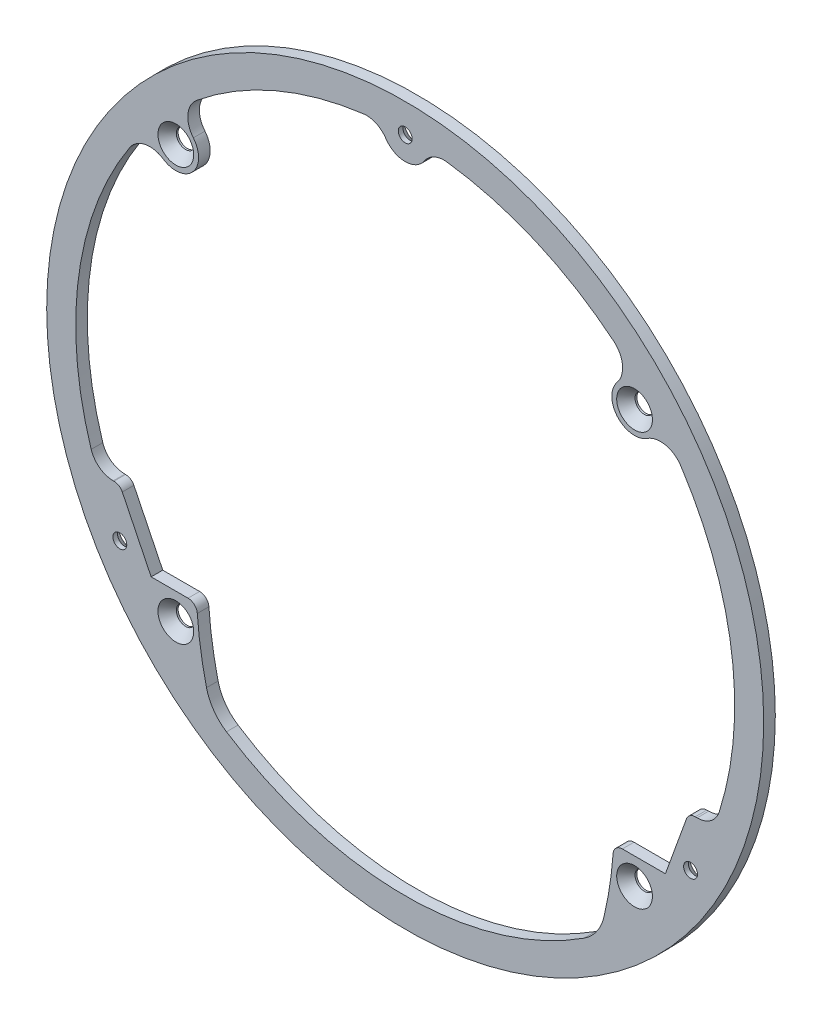
SolidWorks part; units mm, degrees
ref_plane "Front Plane" through (0, 0, 0) normal (0, 0, 1) x (1, 0, 0)
ref_plane "Top Plane" through (0, 0, 0) normal (0, 1, 0) x (1, 0, 0)
ref_plane "Right Plane" through (0, 0, 0) normal (1, 0, 0) x (0, 0, -1)
sketch "Sketch1" plane through (0, 0, 0) normal (0, 0, 1) x (1, 0, 0)
  circle A0 centre (0, 0) radius 98.1075
  circle A1 centre (0, 0) radius 90.17
  dimension "D1" = 196.215
  dimension "D2" = 180.34
extrude "Boss-Extrude1" add sketch "Sketch1" along normal blind 3.175
sketch "Sketch2" plane through (0, 0, 3.175) normal (0, 0, 1) x (1, 0, 0)
  circle A1 centre (0, 0) radius 90.17 construction
  arc A5 (-5.2915, 86.6596) -> (5.2915, 86.6596) centre (0, 90.17) ccw
  circle A6 centre (0, 0) radius 90.17 construction
  arc A8 (-5.2915, 86.6596) -> (-11.3847, 89.4484) centre (-10.5829, 83.1492) ccw
  arc A9 (5.2915, 86.6596) -> (11.3847, 89.4484) centre (10.5829, 83.1492) cw
  arc A10 (11.3847, 89.4484) -> (-11.3847, 89.4484) centre (0, 0) ccw
  dimension "D3" = 6.35
  dimension "D4" = 6.35
extrude "Boss-Extrude2" add sketch "Sketch2" against normal up to surface (3.175 mm away) up to face at (98.1075, 0, 0)
sketch "Sketch9" plane through (0, 0, 3.175) normal (0, 0, 1) x (1, 0, 0)
  line L0 (0, 0) -> (62.7623, -56.5114) construction
  line L1 (0, 0) -> (0, -50000) construction
  arc A0 (66.2123, -51.3323) -> (57.9722, -60.4839) centre (62.7623, -56.5114) ccw
  arc A1 (57.9722, -60.4839) -> (57.0685, -69.8127) centre (52.8889, -64.6997) cw
  arc A2 (66.2123, -51.3323) -> (75.3955, -49.4585) centre (69.8736, -45.8362) ccw
  arc A3 (-11.3847, 89.4484) -> (11.3847, 89.4484) centre (0, 0) ccw construction
  arc A5 (57.0685, -69.8127) -> (75.3955, -49.4585) centre (0, 0) ccw
  dimension "D2" = 6.223
  dimension "D4" = 6.604
  dimension "D1" = 48
  dimension "D3" = 84.455
extrude "Boss-Extrude3" add sketch "Sketch9" against normal up to surface (3.175 mm away) up to face at (98.1075, 0, 0)
sketch "Sketch11" plane through (0, 0, 0) normal (0, 0, 1) x (1, 0, 0)
  line L0 (44.45, -44.45) -> (-44.45, -44.45) construction
  line L1 (0, 0) -> (0, 22.9882) construction
  arc A0 (48.9116, -13.1485) -> (-48.9116, -13.1485) centre (0, -88.9) ccw
  arc A1 (-54.3759, -20.8703) -> (-54.3759, -68.0297) centre (44.45, -44.45) ccw
  arc A2 (-48.9116, -75.7515) -> (48.9116, -75.7515) centre (0, 0) ccw
  arc A3 (-48.9116, -75.7515) -> (-54.3759, -68.0297) centre (-42.0227, -65.0822) cw
  arc A4 (48.9116, -75.7515) -> (54.3759, -68.0297) centre (42.0227, -65.0822) ccw
  arc A5 (54.3759, -68.0297) -> (54.3759, -20.8703) centre (-44.45, -44.45) ccw
  arc A6 (48.9116, -13.1485) -> (54.3759, -20.8703) centre (42.0227, -23.8178) cw
  arc A7 (-48.9116, -13.1485) -> (-54.3759, -20.8703) centre (-42.0227, -23.8178) ccw
  arc A8 (-11.3847, 89.4484) -> (57.0685, -69.8127) centre (0, 0) ccw construction
  arc A9 (-60.5525, -19.3966) -> (-60.5525, -69.5034) centre (44.45, -44.45) ccw
  arc A10 (-52.3561, -81.0861) -> (-60.5525, -69.5034) centre (-42.0227, -65.0822) cw
  arc A11 (-52.3561, -81.0861) -> (52.3561, -81.0861) centre (0, 0) ccw
  arc A12 (52.3561, -81.0861) -> (60.5525, -69.5034) centre (42.0227, -65.0822) ccw
  arc A13 (60.5525, -69.5034) -> (60.5525, -19.3966) centre (-44.45, -44.45) ccw
  arc A14 (52.3561, -7.8139) -> (60.5525, -19.3966) centre (42.0227, -23.8178) cw
  arc A15 (52.3561, -7.8139) -> (-52.3561, -7.8139) centre (0, -88.9) ccw
  arc A16 (-52.3561, -7.8139) -> (-60.5525, -19.3966) centre (-42.0227, -23.8178) ccw
  dimension "D1" = 12.7
  dimension "D4" = 101.6
  dimension "D2" = 44.45
  dimension "D3" = 88.9
  dimension "D5" = 6.35
extrude "Boss-Extrude5" add sketch "Sketch11" along normal up to surface (3.175 mm away) up to face at (98.1075, 0, 3.175)
hole_wizard "CSK for #10 Flat Head Machine Screw1" positions "Sketch4" profile "Sketch3" countersink size "#10" standard "ANSI Inch" end condition through all
sketch "Sketch4" plane through (0, 0, 3.175) normal (0, 0, 1) x (1, 0, 0)
  arc A0 (66.2123, -51.3323) -> (63.3405, -50.3153) centre (62.7623, -56.5114) ccw construction
  point P0 (62.7623, -56.5114)
sketch "Sketch3" plane through (62.7623, -56.5114, 3.175) normal (1, 0, 0) x (0, -1, 0)
  line L0 (0, 0) -> (0, 3.175)
  line L1 (0, 3.175) -> (2.5527, 3.175)
  line L2 (2.5527, 3.175) -> (2.5527, 2.6882)
  line L3 (2.5527, 2.6882) -> (4.8895, 0)
  line L5 (4.8895, 0) -> (0, 0)
  line L6 (-2.5527, 2.6882) -> (-4.8895, 0) construction
  line L11 (0, -6.35) -> (0, 107.95) construction
  dimension "Thru Hole Dia." = 5.1054
  dimension "Thru Hole Depth" = 3.175
  dimension "Near C'Sink Dia." = 9.779
  dimension "Near C'Sink Angle" = 82
hole_wizard "CSK for #6 Flat Head Machine Screw1" positions "Sketch8" profile "Sketch7" countersink size "#6" standard "ANSI Inch" end condition through all
sketch "Sketch8" plane through (0, 0, 0) normal (0, 0, -1) x (-1, 0, 0)
  point P0 (0, 90.17)
sketch "Sketch7" plane through (0, 90.17, 0) normal (1, 0, 0) x (0, 1, 0)
  line L0 (0, 0) -> (0, 3.175)
  line L1 (0, 3.175) -> (1.8986, 3.175)
  line L2 (1.8986, 3.175) -> (1.8986, 1.892)
  line L3 (1.8986, 1.892) -> (3.5433, 0)
  line L5 (3.5433, 0) -> (0, 0)
  line L6 (-1.8986, 1.892) -> (-3.5433, 0) construction
  line L11 (0, -6.35) -> (0, 107.95) construction
  dimension "Thru Hole Dia." = 3.7973
  dimension "Thru Hole Depth" = 3.175
  dimension "Near C'Sink Dia." = 7.0866
  dimension "Near C'Sink Angle" = 82
mirror "Mirror1" about plane through (0, 0, 0) normal (0, 1, 0) of "CSK for #10 Flat Head Machine Screw1", "Boss-Extrude3"
mirror "Mirror2" about plane through (0, 0, 0) normal (1, 0, 0) of "Mirror1", "Boss-Extrude3", "CSK for #10 Flat Head Machine Screw1"
pattern_circular "CirPattern1" count 3 over 360 about axis through (0, 0, 0) along (0, 0, 1) of "Boss-Extrude2", "CSK for #6 Flat Head Machine Screw1"
fillet "Fillet1" radius 3.175 2 edges at (-63.3405, -50.3153, 1.5875) (63.3405, -50.3153, 1.5875)
sketch "Sketch13" plane through (0, 0, 3.175) normal (0, 0, 1) x (1, 0, 0)
  line L0 (-84.3953, -31.75) -> (-62.7503, -31.75)
  line L3 (62.7503, -31.75) -> (84.3953, -31.75)
  arc A6 (-75.3955, 49.4585) -> (-83.1569, -34.8648) centre (0, 0) ccw construction
  arc A7 (-60.5525, -19.3966) -> (-63.4467, -47.842) centre (44.45, -44.45) ccw construction
  arc A8 (63.4467, -47.842) -> (60.5525, -19.3966) centre (-44.45, -44.45) ccw construction
  arc A9 (83.1569, -34.8648) -> (75.3955, 49.4585) centre (0, 0) ccw construction
  arc M9 (-60.5525, -19.3966) -> (-63.4467, -47.842) centre (44.45, -44.45) ccw
  arc M10 (-63.4467, -47.842) -> (-65.3168, -50.8369) centre (-66.6201, -47.9417) cw
  arc M12 (-72.4037, -47.9124) -> (-77.6952, -38.7473) centre (-78.0895, -45.085) ccw
  arc M13 (-77.6952, -38.7473) -> (-83.1569, -34.8648) centre (-77.3008, -32.4095) cw
  arc M14 (-83.1569, -34.8648) -> (-75.3955, 49.4585) centre (0, 0) cw
  arc M26 (75.3955, 49.4585) -> (83.1569, -34.8648) centre (0, 0) cw
  arc M27 (83.1569, -34.8648) -> (77.6952, -38.7473) centre (77.3008, -32.4095) cw
  arc M28 (77.6952, -38.7473) -> (72.4037, -47.9124) centre (78.0895, -45.085) ccw
  arc M30 (65.3168, -50.8369) -> (63.4467, -47.842) centre (66.6201, -47.9417) cw
  arc M31 (63.4467, -47.842) -> (60.5525, -19.3966) centre (-44.45, -44.45) ccw
  arc M57 (-65.3168, -50.8369) -> (-66.2123, -51.3323) centre (-62.7623, -56.5114) ccw
  arc M59 (66.2123, -51.3323) -> (65.3168, -50.8369) centre (62.7623, -56.5114) ccw
  arc M95 (72.4037, -47.9124) -> (73.002, -51.6522) centre (66.7179, -50.7397) cw
  arc M96 (73.002, -51.6522) -> (66.2123, -51.3323) centre (69.8736, -45.8362) cw
  arc M97 (-66.2123, -51.3323) -> (-73.002, -51.6522) centre (-69.8736, -45.8362) cw
  arc M98 (-73.002, -51.6522) -> (-72.4037, -47.9124) centre (-66.7179, -50.7397) cw
  dimension "D1" = 31.75
extrude "Boss-Extrude6" add sketch "Sketch13" against normal up to surface (3.175 mm away) contours L0 M14 M13 M12 M98 M97 M57 M10 M9 | L3 M31 M30 M59 M96 M95 M28 M27 M26 up to face at (-81.6328, -45.085, 0)
fillet "Fillet2" radius 6.35 4 edges at (84.3953, -31.75, 1.5875) (-62.7503, -31.75, 1.5875) (62.7503, -31.75, 1.5875) (-84.3953, -31.75, 1.5875)
hole_wizard "#6 Clearance Hole1" positions "Sketch15" profile "Sketch14" hole size "#6" standard "ANSI Inch"
sketch "Sketch15" plane through (0, 0, 3.175) normal (0, 0, 1) x (1, 0, 0)
  line L0 (0, 0.3556) -> (0, -49999.6444) construction
  arc A0 (48.9116, -13.1485) -> (-48.9116, -13.1485) centre (0, -88.9) ccw construction
  arc A1 (-54.3759, -20.8703) -> (-54.3759, -68.0297) centre (44.45, -44.45) ccw construction
  point P0 (-66.675, -44.45)
  point P2 (66.675, -44.45)
  point P10 (0, 1.27)
  point P13 (-57.15, -44.45)
  dimension "D1" = 9.525
sketch "Sketch14" plane through (-66.675, -44.45, 3.175) normal (1, 0, 0) x (0, -1, 0)
  line L0 (0, 0) -> (0, 7.4908)
  line L1 (0, 7.4908) -> (1.8986, 6.35)
  line L2 (1.8986, 6.35) -> (1.8986, 0)
  line L5 (1.8986, 0) -> (0, 0)
  line L10 (0, 7.4908) -> (-1.8986, 6.35) construction
  line L11 (0, -6.35) -> (0, 107.95) construction
  dimension "Hole Dia." = 3.7973
  dimension "Hole Depth" = 6.35
  dimension "Drill Angle" = 118
sketch "Sketch16" plane through (0, 0, 3.175) normal (0, 0, 1) x (1, 0, 0)
  line L0 (-79.5737, -28.7581) -> (-69.5168, -49.3359)
  line L1 (-54.9731, -49.3359) -> (-69.5168, -49.3359)
  line L2 (-54.9731, -49.3359) -> (71.2008, -49.3359)
  line L3 (71.2008, -49.3359) -> (78.6614, -28.7581)
  line L5 (-79.5737, -28.7581) -> (-79.5737, 37.9939)
  line L6 (-79.5737, 37.9939) -> (74.9311, 37.9939)
  line L7 (74.9311, 37.9939) -> (78.6614, -28.7581)
extrude "Cut-Extrude1" cut sketch "Sketch16" against normal through all
fillet "Fillet3" radius 2.54 4 edges at (77.5767, -31.75, 1.5875) (57.0325, -49.3359, 1.5875) (-78.1115, -31.75, 1.5875) (-57.0325, -49.3359, 1.5875)
